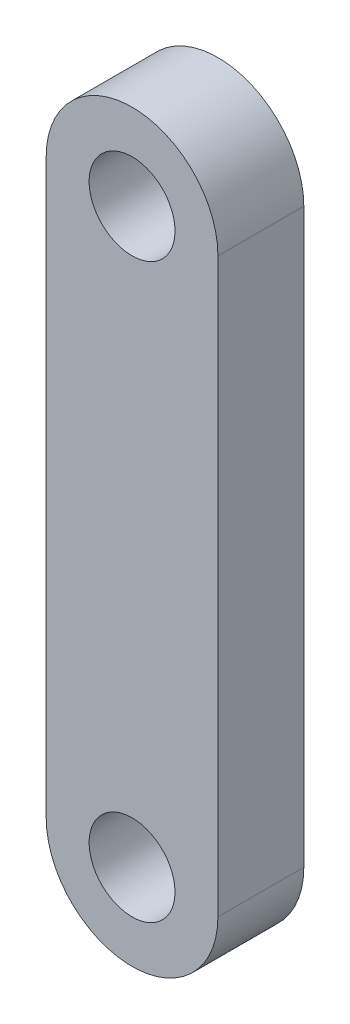
SolidWorks part; units mm, degrees
ref_plane "Front Plane" through (0, 0, 0) normal (0, 0, 1) x (1, 0, 0)
ref_plane "Top Plane" through (0, 0, 0) normal (0, 1, 0) x (1, 0, 0)
ref_plane "Right Plane" through (0, 0, 0) normal (1, 0, 0) x (0, 0, -1)
sketch "Sketch2" plane through (0, 0, 0) normal (0, 0, 1) x (1, 0, 0)
  line L0 (0, 20) -> (0, -20) construction
  line L1 (6, 20) -> (6, -20)
  line L2 (-6, 20) -> (-6, -20)
  arc A0 (6, 20) -> (-6, 20) centre (0, 20) ccw
  arc A1 (-6, -20) -> (6, -20) centre (0, -20) ccw
  circle A2 centre (0, 20) radius 3
  circle A3 centre (0, -20) radius 3
  point P2 (0, 0)
  dimension "D2" = 6
  dimension "D3" = 6
  dimension "D4" = 6
  dimension "D1" = 40
extrude "Boss-Extrude1" add sketch "Sketch2" against normal blind 6
scale "Scale1" scale about centroid uniform scaling yes scale factor 0.5
